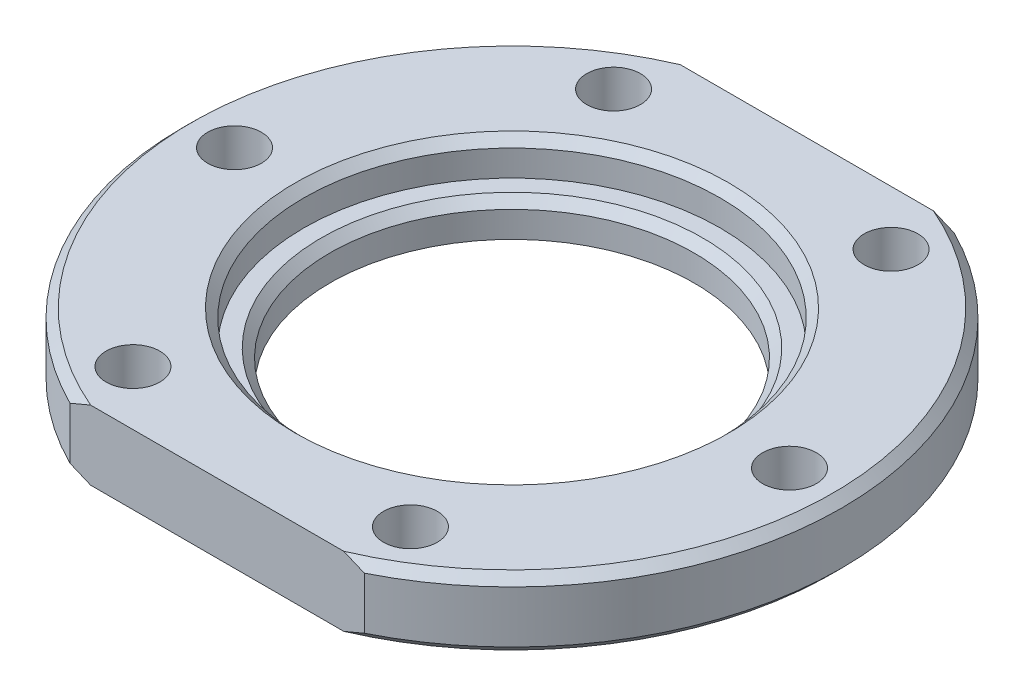
SolidWorks part; units mm, degrees
ref_plane "Front Plane" through (0, 0, 0) normal (0, 0, 1) x (1, 0, 0)
ref_plane "Top Plane" through (0, 0, 0) normal (0, 1, 0) x (1, 0, 0)
ref_plane "Right Plane" through (0, 0, 0) normal (1, 0, 0) x (0, 0, -1)
sketch "Sketch1" plane through (0, 0, 0) normal (0, 1, 0) x (1, 0, 0)
  line L0 (-8.4853, 17) -> (8.4853, 17)
  line L1 (-8.4853, -17) -> (8.4853, -17)
  arc A0 (-8.4853, 17) -> (-8.4853, -17) centre (0, 0) ccw
  circle A1 centre (0, 0) radius 16 construction
  circle A2 centre (0, 0) radius 10.5
  circle A3 centre (-16, 0) radius 1.55
  circle A4 centre (-8, 13.8564) radius 1.55
  circle A5 centre (8, 13.8564) radius 1.55
  circle A6 centre (16, 0) radius 1.55
  circle A7 centre (8, -13.8564) radius 1.55
  circle A8 centre (-8, -13.8564) radius 1.55
  arc A9 (8.4853, -17) -> (8.4853, 17) centre (0, 0) ccw
  point P19 (0, 0)
  point P22 (0, 0)
  point P23 (0, 0)
  point P24 (0, 0)
  dimension "D1" = 38
  dimension "D2" = 32
  dimension "D3" = 21
  dimension "D4" = 3.1
  dimension "D6" = 17
  dimension "D7" = 17
  dimension "D5" = 6
extrude "Boss-Extrude1" add sketch "Sketch1" along normal blind 4
sketch "Sketch2" plane through (0, 4, 0) normal (0, 1, 0) x (1, 0, 0)
  circle A0 centre (0, 0) radius 12
  dimension "D1" = 24
extrude "Cut-Extrude1" cut sketch "Sketch2" against normal blind 2
chamfer "Chamfer1" distance 0.5 angle 45 6 edges at (-19, 0, 0) (19, 0, 0) (19, 4, 0) (0, 2, 10.5) (0, 4, 12) (-19, 4, 0)
